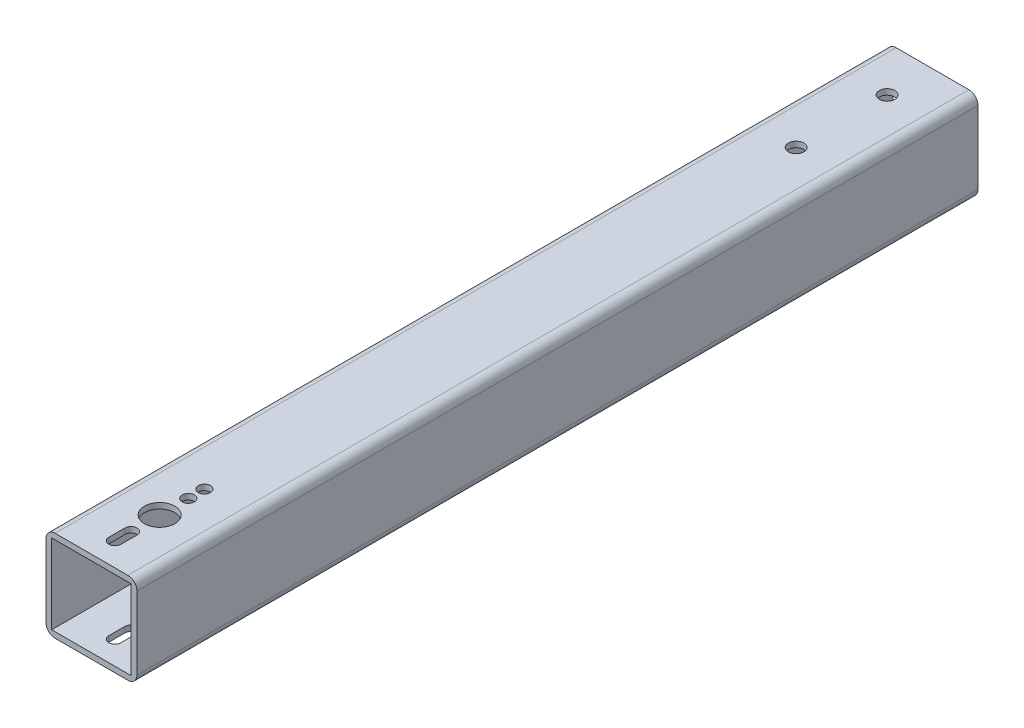
SolidWorks part; units mm, degrees
ref_plane "Front Plane" through (0, 0, 0) normal (0, 0, 1) x (1, 0, 0)
ref_plane "Top Plane" through (0, 0, 0) normal (0, 1, 0) x (1, 0, 0)
ref_plane "Right Plane" through (0, 0, 0) normal (1, 0, 0) x (0, 0, -1)
sketch "Sketch1" plane through (0, 0, 0) normal (0, 0, 1) x (1, 0, 0)
  line L1 (-24.2596, 11.4248) -> (1.1404, 11.4248)
  line L2 (-24.2596, 11.4248) -> (-24.2596, -13.9752)
  line L3 (-24.2596, -13.9752) -> (1.1404, -13.9752)
  line L4 (1.1404, 11.4248) -> (1.1404, -13.9752)
  line L5 (-22.6721, 9.8373) -> (-0.4471, 9.8373)
  line L6 (-22.6721, 9.8373) -> (-22.6721, -12.3877)
  line L7 (-22.6721, -12.3877) -> (-0.4471, -12.3877)
  line L8 (-0.4471, 9.8373) -> (-0.4471, -12.3877)
  dimension "D1" = 25.4
  dimension "D2" = 25.4
  dimension "D3" = 1.5875
  dimension "D4" = 1.5875
  dimension "D5" = 1.5875
  dimension "D6" = 1.5875
extrude "Boss-Extrude1" add sketch "Sketch1" along normal blind 234.95
fillet "Fillet1" radius 2.54 4 edges at (1.1404, -13.9752, 117.475) (-24.2596, -13.9752, 117.475) (-24.2596, 11.4248, 117.475) (1.1404, 11.4248, 117.475)
sketch "Sketch2" plane through (0, 11.4248, 0) normal (0, 1, 0) x (1, 0, 0)
  line L0 (-1.3996, 0) -> (-21.7196, 0) construction
  line L1 (0, 0) -> (0, -59.7417) construction
  line L2 (-11.5596, -12.7) -> (-11.5596, 0) construction
  line L3 (-1.3996, -234.95) -> (-1.3996, 0) construction
  line L4 (-21.7196, -50.8) -> (29.3119, -50.8) construction
  line L5 (-21.7196, 0) -> (-21.7196, -234.95) construction
  circle A0 centre (-11.5596, -12.7) radius 2.159
  circle A2 centre (-11.5596, -38.1) radius 2.159
  dimension "D1" = 4.318
  dimension "D2" = 12.7
  dimension "D3" = 4.318
  dimension "D4" = 50.8
  dimension "D6" = 25.4
extrude "Cut-Extrude1" cut sketch "Sketch2" against normal through all
sketch "Sketch3" plane through (0, 11.4248, 0) normal (0, 1, 0) x (1, 0, 0)
  line L0 (-11.5596, -215.9) -> (-15.3182, -190.7796) construction
  line L1 (-11.5596, -215.9) -> (13.426, -212.1616) construction
  line L2 (-11.5596, -215.9) -> (-29.2422, -202.8202) construction
  line L3 (-11.5596, -215.9) -> (-11.5596, -196.7728) construction
  line L5 (-11.5596, -223.9) -> (-11.5596, -228.4) construction
  line L6 (-9.8596, -223.9) -> (-9.8596, -228.4)
  line L7 (-13.2596, -223.9) -> (-13.2596, -228.4)
  line L8 (-11.5596, -207.9) -> (-11.5596, -223.9) construction
  line L11 (-11.5596, -215.9) -> (30.1254, -215.9) construction
  line L12 (-37.8321, -50.8) -> (104.3326, -50.8) construction
  line L13 (-1.3996, 0) -> (-21.7196, 0) construction
  circle A0 centre (-11.5596, -207.9) radius 1.7
  circle A1 centre (-11.5596, -203.4) radius 1.7
  circle A2 centre (-11.5596, -215.9) radius 20.9 construction
  circle A3 centre (-11.5596, -215.9) radius 4.25
  arc A6 (-9.8596, -223.9) -> (-13.2596, -223.9) centre (-11.5596, -223.9) ccw
  arc A7 (-13.2596, -228.4) -> (-9.8596, -228.4) centre (-11.5596, -228.4) ccw
  point P17 (-11.5596, -196.9907)
  point P21 (-11.5596, -226.15)
  point P33 (-11.5596, 0)
  dimension "D1" = 215.9
  dimension "D2" = 3.4
  dimension "D3" = 3.4
  dimension "D4" = 8.5
  dimension "D13" = 41.8
  dimension "D5" = 12.5
  dimension "D8" = 25
  dimension "D7" = 16
  dimension "D9" = 8
  dimension "D6" = 3.4
  dimension "D10" = 8
  dimension "D14" = 50.8
extrude "Cut-Extrude2" cut sketch "Sketch3" against normal through all and the other way through all
